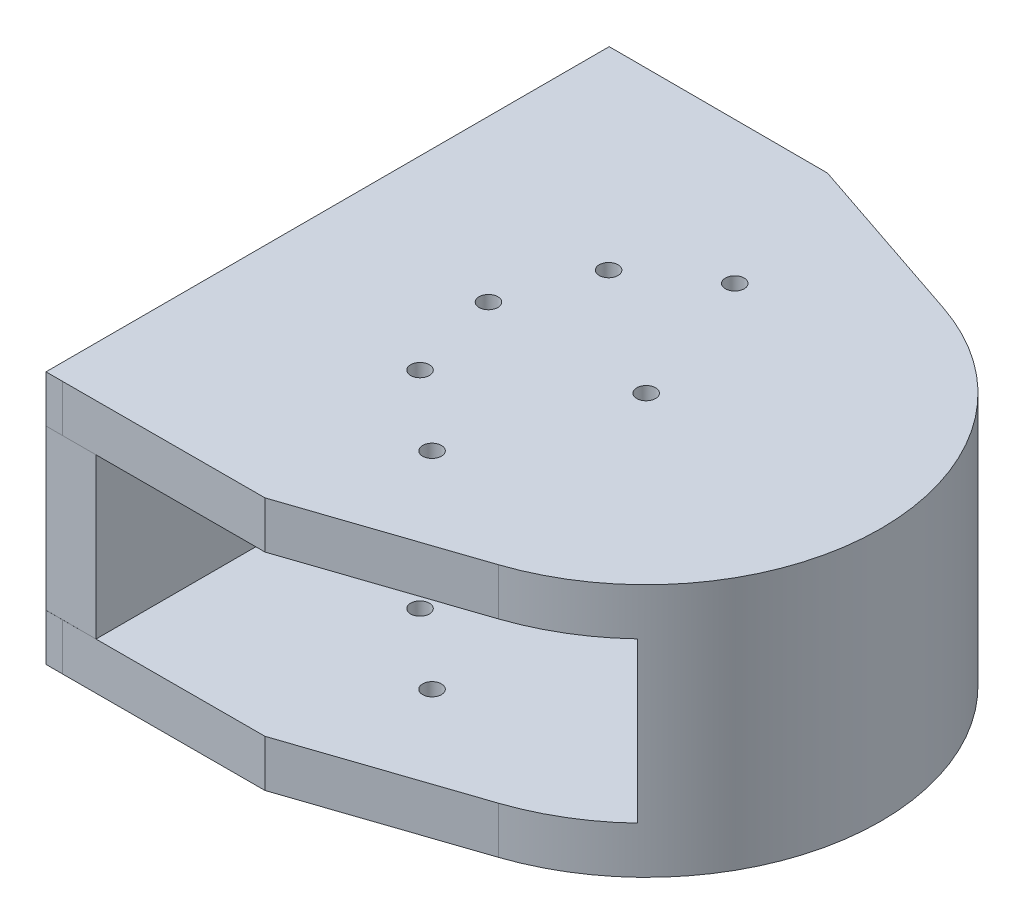
SolidWorks part; units mm, degrees
ref_plane "Front Plane" through (0, 0, 0) normal (0, 0, 1) x (1, 0, 0)
ref_plane "Top Plane" through (0, 0, 0) normal (0, 1, 0) x (1, 0, 0)
ref_plane "Right Plane" through (0, 0, 0) normal (1, 0, 0) x (0, 0, -1)
sketch "Sketch1" plane through (0, 0, 0) normal (0, 1, 0) x (1, 0, 0)
  line L0 (-16.8, 0) -> (0, 0) construction
  line L3 (-10.6469, -29.9647) -> (-10.6469, 29.9647) construction
  line L4 (-16.8, 0) -> (-10.6469, 0) construction
  line L5 (-10.6469, 0) -> (-31.8, 0) construction
  line L6 (0, 0) -> (-13.3522, 9.3493)
  line L8 (-5.4039, 14.8471) -> (0, 0)
  line L9 (0, 0) -> (-6.088, -16.7265)
  line L11 (-14.1713, -9.9229) -> (0, 0)
  line L15 (-32.1601, -30) -> (-28.6178, -29.9942)
  line L16 (-31.4399, 30) -> (-27.9817, 29.9941)
  line L17 (-10.6469, -29.9647) -> (7.9784, -23.6927)
  line L18 (-10.6469, 29.9647) -> (7.9784, 23.6927)
  line L19 (-11.1494, 26.4408) -> (-10.6469, 26.2716)
  line L21 (-28.6178, -26.4942) -> (-27.9817, 26.4941)
  line L24 (-32.1601, -30) -> (-33.9399, -30)
  line L25 (-33.9399, -30) -> (-33.9399, 30)
  line L26 (-33.9399, 30) -> (-31.4399, 30)
  line L27 (-32.1601, -30) -> (-31.4399, 30) construction
  line L28 (14.7933, 15.6016) -> (17.2015, 18.1414)
  line L29 (-27.9817, 26.4941) -> (-27.9817, 29.9941)
  line L30 (-28.6178, -26.4942) -> (-28.6178, -29.9942)
  line L31 (-11.2232, 26.4657) -> (6.8615, 20.3757) construction
  line L32 (-27.9817, 26.4941) -> (-11.2232, 26.4657) construction
  line L33 (-28.6178, -26.4942) -> (-11.2231, -26.4657) construction
  line L34 (-11.2231, -26.4657) -> (6.8615, -20.3757) construction
  line L35 (14.7933, -15.6016) -> (17.2015, -18.1414)
  line L36 (-27.9817, 29.9941) -> (-10.6469, 29.9647)
  line L37 (-31.4399, 30) -> (-10.6469, 29.9647) construction
  line L38 (-28.6178, -29.9942) -> (-10.6469, -29.9647)
  line L39 (-32.1601, -30) -> (-10.6469, -29.9647) construction
  circle A0 centre (0, 0) radius 1
  circle A1 centre (-16.8, 0) radius 1
  arc A2 (7.9784, -23.6927) -> (17.2015, -18.1414) centre (0, 0) ccw
  arc A3 (-31.7908, 0.7633) -> (-31.8, 0) centre (0, 0) ccw
  circle A4 centre (-13.3522, 9.3493) radius 1
  circle A5 centre (-5.4039, 14.8471) radius 1
  circle A6 centre (-14.1713, -9.9229) radius 1
  circle A7 centre (-6.088, -16.7265) radius 1
  arc A10 (14.7933, -15.6016) -> (14.7933, 15.6016) centre (0, 0) ccw
  arc A11 (6.8615, -20.3757) -> (6.8615, 20.3757) centre (0, 0) ccw construction
  arc A12 (17.2015, -18.1414) -> (17.2015, 18.1414) centre (0, 0) ccw
  arc A13 (7.9784, -23.6927) -> (7.9784, 23.6927) centre (0, 0) ccw construction
  arc A14 (17.2015, 18.1414) -> (7.9784, 23.6927) centre (0, 0) ccw
  point P39 (-39.7061, -56.1149)
  dimension "D1" = 2
  dimension "D2" = 2
  dimension "D3" = 50
  dimension "D7" = 2
  dimension "D8" = 2
  dimension "D9" = 2
  dimension "D10" = 2
  dimension "D4" = 15
  dimension "D5" = 16.8
  dimension "D6" = 3.5
  dimension "D11" = 35
  dimension "D12" = 35
  dimension "D13" = 35
  dimension "D14" = 35
  dimension "D15" = 16.3
  dimension "D16" = 15.8
  dimension "D17" = 17.3
  dimension "D18" = 17.8
  dimension "D19" = 60
  dimension "D20" = 2.5
  dimension "D21" = 1.7798
extrude "Boss-Extrude2" add sketch "Sketch1" along normal blind 5 contours A2 A12 A14 L18 L36 L16 L26 L25 L24 L15 L38 L17
sketch "Sketch5" plane through (0, 0, 0) normal (0, -1, 0) x (1, 0, 0)
  line L1 (-33.9399, -30) -> (-28.6178, -30)
  line L2 (-33.9399, -30) -> (-33.9399, 29.9942)
  line L3 (-33.9399, 29.9942) -> (-28.6178, 29.9942)
  line L4 (-28.6178, -30) -> (-28.6178, 29.9942)
extrude "Boss-Extrude4" add sketch "Sketch5" along normal blind 8.5
sketch "Sketch6" plane through (0, 0, 0) normal (0, -1, 0) x (1, 0, 0)
  line L0 (14.7933, 15.6016) -> (17.2015, 18.1414)
  line L1 (15.6016, -14.7933) -> (17.4297, -17.9222)
  arc A0 (17.2015, 18.1414) -> (17.4297, -17.9222) centre (0, 0) cw
  arc A1 (14.7933, 15.6016) -> (15.6016, -14.7933) centre (0, 0) cw
extrude "Boss-Extrude5" add sketch "Sketch6" along normal blind 8.5
sketch "Sketch7" plane through (0, 0, 0) normal (0, -1, 0) x (1, 0, 0)
  circle A0 centre (-6.088, 16.7265) radius 1
  circle A1 centre (0, 0) radius 1
  circle A2 centre (-14.1713, 9.9229) radius 1
  circle A3 centre (-16.8, 0) radius 1
  circle A4 centre (-13.3522, -9.3493) radius 1
  circle A5 centre (-5.4039, -14.8471) radius 1
  dimension "D1" = 2
  dimension "D2" = 2
  dimension "D3" = 2
  dimension "D4" = 2
  dimension "D5" = 2
  dimension "D6" = 2
extrude "Cut-Extrude1" cut sketch "Sketch7" against normal blind 8.5
mirror "Mirror1" about plane through (0, -8.5, 0) normal (0, 1, 0) of bodies 105
